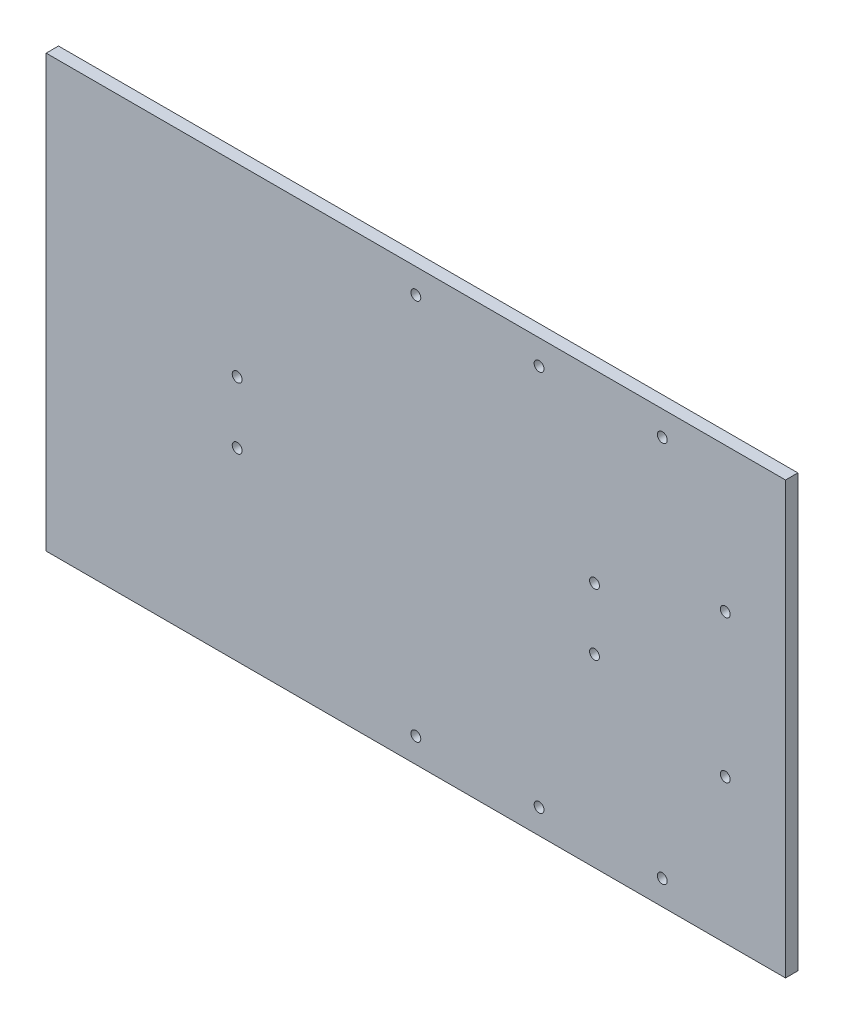
SolidWorks part; units mm, degrees
ref_plane "Front Plane" through (0, 0, 0) normal (0, 0, 1) x (1, 0, 0)
ref_plane "Top Plane" through (0, 0, 0) normal (0, 1, 0) x (1, 0, 0)
ref_plane "Right Plane" through (0, 0, 0) normal (1, 0, 0) x (0, 0, -1)
sketch "Sketch1" plane through (0, 0, 0) normal (0, 0, 1) x (1, 0, 0)
  line L1 (0, 0) -> (-600, 0)
  line L2 (0, 0) -> (0, 350)
  line L3 (0, 350) -> (-600, 350)
  line L4 (-600, 0) -> (-600, 350)
  dimension "D1" = 600
  dimension "D2" = 350
extrude "Boss-Extrude1" add sketch "Sketch1" along normal blind 10
sketch "Sketch2" plane through (0, 0, 0) normal (0, 0, -1) x (-1, 0, 0)
  line L0 (0, 350) -> (600, 350) construction
  line L1 (0, 0) -> (0, 350) construction
  line L2 (0, 175) -> (600, 175) construction
  line L3 (600, 350) -> (600, 0) construction
  line L4 (300, 359.8036) -> (300, 110.2891) construction
  circle A3 centre (100, 330) radius 4
  circle A4 centre (200, 330) radius 4
  circle A5 centre (300, 330) radius 4
  circle A6 centre (300, 20) radius 4
  circle A7 centre (200, 20) radius 4
  circle A8 centre (100, 20) radius 4
  dimension "D1" = 8
  dimension "D6" = 200
  dimension "D2" = 20
  dimension "D3" = 20
  dimension "D4" = 20
  dimension "D5" = 100
  dimension "D7" = 300
extrude "Cut-Extrude1" cut sketch "Sketch2" against normal blind 10
sketch "Sketch4" plane through (0, 0, 0) normal (0, 0, -1) x (-1, 0, 0)
  line L1 (600, 175) -> (0, 175) construction
  line L2 (300, 175) -> (300, 67.3523) construction
  line L4 (0, 350) -> (0, 0) construction
  circle A0 centre (155, 150) radius 4
  circle A1 centre (155, 200) radius 4
  circle A2 centre (445, 150) radius 4
  circle A3 centre (445, 200) radius 4
  circle A4 centre (100, 20) radius 4 construction
  point P6 (155, 150)
  point P7 (300, 175)
  dimension "D4" = 8
  dimension "D2" = 25
  dimension "D3" = 145
  dimension "D1" = 55
  dimension "D5" = 130
sketch "Sketch9" plane through (0, 0, 0) normal (0, 0, -1) x (-1, 0, 0)
  line L0 (0, 0) -> (0, 350) construction
  line L1 (0, 175) -> (349.8207, 175) construction
  circle A0 centre (48.9146, 233) radius 4
  circle A2 centre (48.9146, 117) radius 4
  dimension "D1" = 8
extrude "Cut-Extrude4" cut sketch "Sketch9" against normal through all
extrude "Cut-Extrude5" cut sketch "Sketch4" against normal up to next
